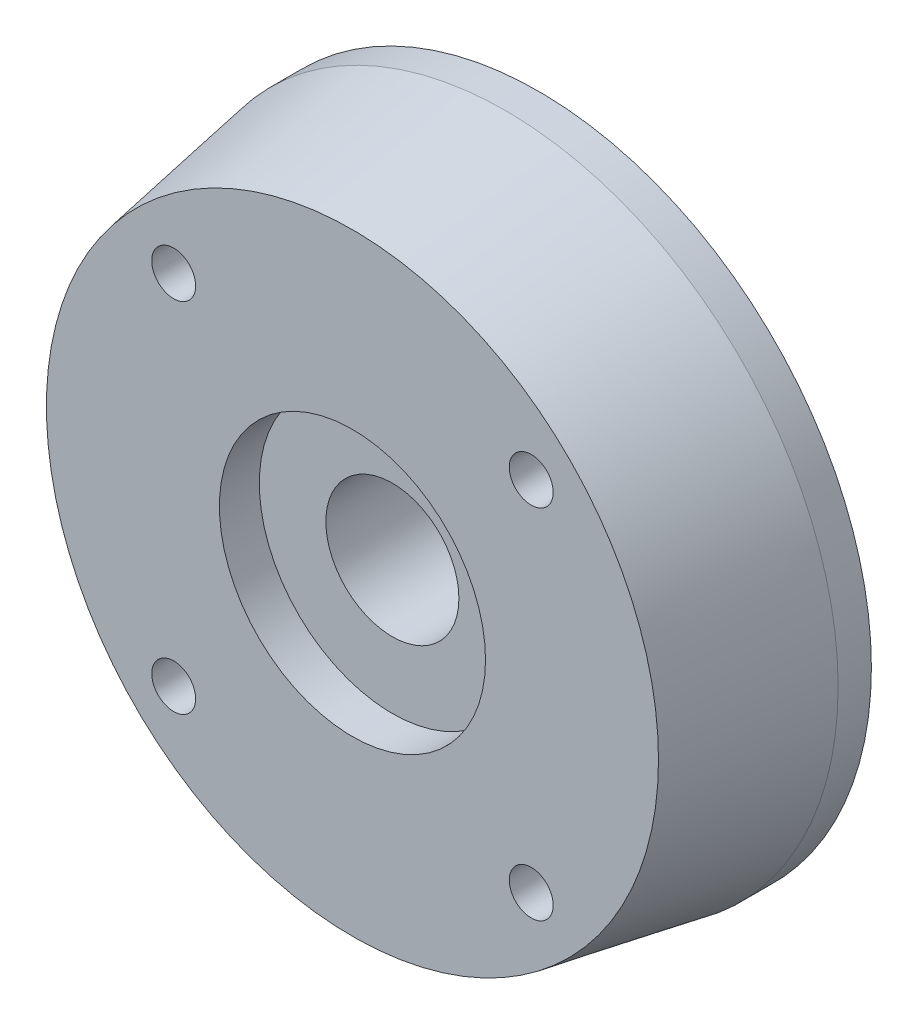
SolidWorks part; units mm, degrees
ref_plane "前视基准面" through (0, 0, 0) normal (0, 0, 1) x (1, 0, 0)
ref_plane "上视基准面" through (0, 0, 0) normal (0, 1, 0) x (1, 0, 0)
ref_plane "右视基准面" through (0, 0, 0) normal (1, 0, 0) x (0, 0, -1)
sketch "草图1" plane through (0, 0, 0) normal (0, 0, 1) x (1, 0, 0)
  circle A0 centre (0, 0) radius 25
  dimension "D1" = 50
extrude "凸台-拉伸1" add sketch "草图1" along normal blind 14
sketch "草图2" plane through (0, 0, 0) normal (1, 0, 0) x (0, 0, -1)
  line L0 (-14, 25) -> (-2.5, 25)
  line L1 (0, 25) -> (-14, 25) construction
  line L2 (-2.5, 25) -> (-14, 23)
  line L3 (-14, 25) -> (-14, -25) construction
  line L4 (-14, 23) -> (-14, 25)
  line L5 (0, 0) -> (10.6183, 0) construction
  line L6 (0, -25) -> (0, 25) construction
  dimension "D1" = 2
  dimension "D2" = 11.5
revolve "切除-旋转1" cut sketch "草图2" angle 360 about L5
sketch "草图3" plane through (0, 0, 14) normal (0, 0, 1) x (1, 0, 0)
  line L0 (0, 0) -> (0, 19) construction
  line L1 (0, 0) -> (13.435, 13.435) construction
  circle A0 centre (0, 0) radius 19 construction
  circle A1 centre (13.435, 13.435) radius 1.5
  dimension "D1" = 38
  dimension "D3" = 3
  dimension "D2" = 45
extrude "切除-拉伸1" cut sketch "草图3" against normal blind 2
hole_wizard "M4 螺纹孔1" positions "3D草图1" profile "草图4" tap size "M4" standard "GB" end condition through all
sketch3d "3D草图1"
  line L0 (13.435, 13.435, 12) -> (13.435, 13.435, 14) construction
  point P0 (13.435, 13.435, 14)
sketch "草图4" plane through (13.435, 13.435, 14) normal (1, 0, 0) x (0, -1, 0)
  line L0 (0, 0) -> (0, 14)
  line L1 (0, 14) -> (1.65, 14)
  line L2 (1.65, 14) -> (1.65, 0)
  line L5 (1.65, 0) -> (0, 0)
  line L11 (0, -6.35) -> (0, 107.95) construction
  dimension "通孔螺纹孔钻头直径" = 3.3
  dimension "通孔螺纹孔钻头深度" = 14
cosmetic thread "孔螺蚊线1" parameters "D2"=4
pattern_circular "阵列(圆周)1" count 4 over 360 about axis through (0, 0, 0) along (0, 0, 1) of "M4 螺纹孔1"
sketch "草图5" plane through (0, 0, 14) normal (0, 0, 1) x (1, 0, 0)
  circle A0 centre (0, 0) radius 10
  dimension "D1" = 20
extrude "切除-拉伸2" cut sketch "草图5" against normal blind 3
sketch "草图6" plane through (0, 0, 11) normal (0, 0, 1) x (1, 0, 0)
  circle A0 centre (0, 0) radius 5
  dimension "D1" = 10
extrude "切除-拉伸3" cut sketch "草图6" against normal through all
